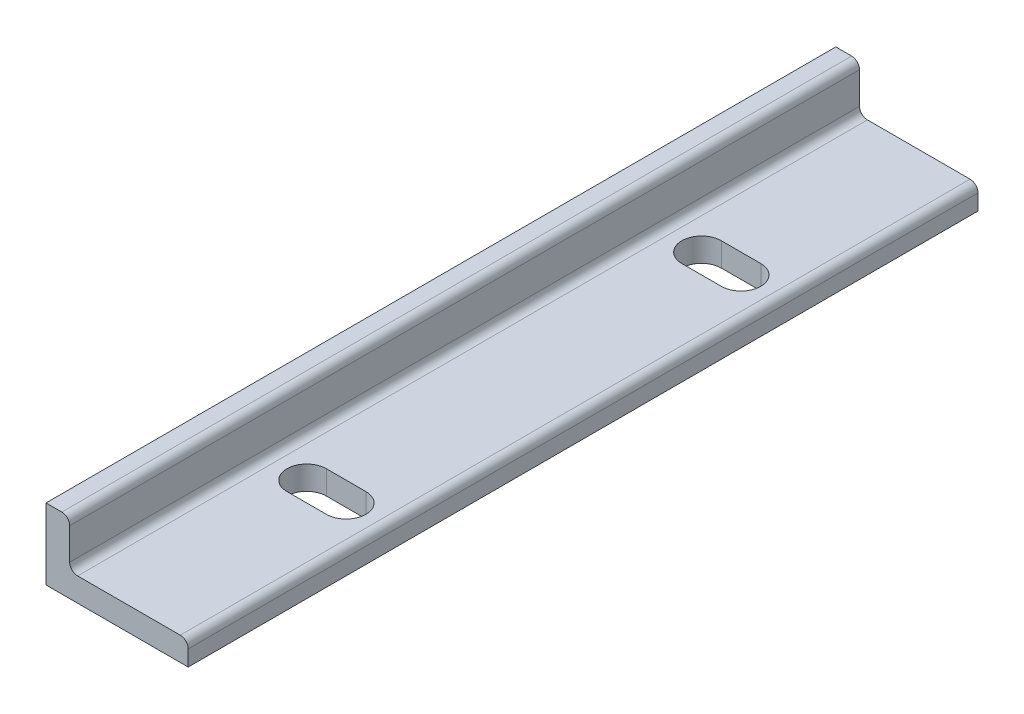
SolidWorks part; units mm, degrees
material "ABS"
ref_plane "Front Plane" through (0, 0, 0) normal (0, 0, 1) x (1, 0, 0)
ref_plane "Top Plane" through (0, 0, 0) normal (0, 1, 0) x (1, 0, 0)
ref_plane "Right Plane" through (0, 0, 0) normal (1, 0, 0) x (0, 0, -1)
sketch "Sketch1" plane through (0, 0, 0) normal (0, 0, 1) x (1, 0, 0)
  line L0 (0, 0) -> (18, 0)
  line L1 (18, 0) -> (18, 3)
  line L2 (18, 3) -> (3, 3)
  line L3 (3, 3) -> (3, 9)
  line L4 (3, 9) -> (0, 9)
  line L5 (0, 9) -> (0, 0)
  dimension "D1" = 9
  dimension "D2" = 3
  dimension "D3" = 3
  dimension "D4" = 18
extrude "Boss-Extrude1" add sketch "Sketch1" along normal blind 100
fillet "Fillet1" radius 1 3 edges at (3, 9, 50) (3, 3, 50) (18, 3, 50)
sketch "Sketch2" plane through (0, 3, 0) normal (0, 1, 0) x (1, 0, 0)
  line L0 (17, 0) -> (4, 0) construction
  line L1 (17, -100) -> (4, -100) construction
  circle A0 centre (10.5, -25) radius 2.5
  circle A1 centre (10.5, -75) radius 2.5
  point P5 (10.5, 0)
  dimension "D1" = 5
  dimension "D3" = 5
  dimension "D2" = 25
  dimension "D4" = 25
extrude "Cut-Extrude1" cut sketch "Sketch2" against normal through all
sketch "Sketch3" plane through (0, 3, 0) normal (0, 1, 0) x (1, 0, 0)
  line L0 (8, -75) -> (13, -75) construction
  line L1 (8, -72.5) -> (13, -72.5)
  line L2 (8, -77.5) -> (13, -77.5)
  line L3 (17, -50) -> (4, -50) construction
  line L4 (17, -100) -> (17, 0) construction
  line L5 (4, 0) -> (4, -100) construction
  line L6 (8, -25) -> (13, -25) construction
  line L7 (8, -27.5) -> (13, -27.5)
  line L8 (8, -22.5) -> (13, -22.5)
  circle A0 centre (10.5, -75) radius 2.5 construction
  arc A1 (8, -72.5) -> (8, -77.5) centre (8, -75) ccw
  arc A2 (13, -77.5) -> (13, -72.5) centre (13, -75) ccw
  arc A4 (8, -27.5) -> (8, -22.5) centre (8, -25) cw
  arc A5 (13, -22.5) -> (13, -27.5) centre (13, -25) cw
  point P5 (10.5, -75)
  point P18 (10.5, -25)
  dimension "D1" = 2.5
extrude "Cut-Extrude2" cut sketch "Sketch3" against normal through all
